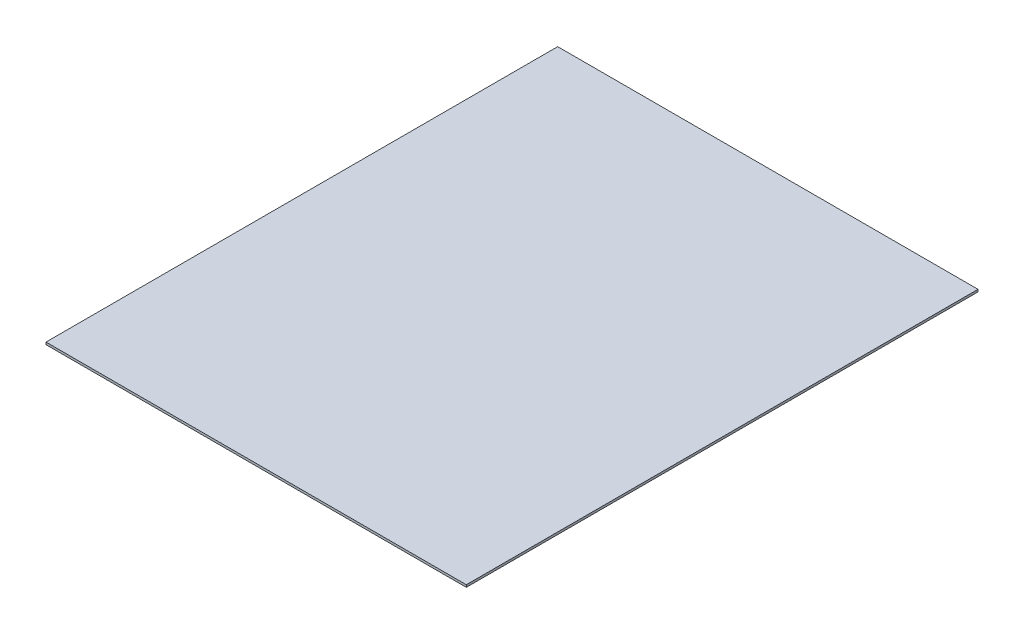
SolidWorks part; units mm, degrees
material "6061-T6 (SS)"
ref_plane "Front Plane" through (0, 0, 0) normal (0, 0, 1) x (1, 0, 0)
ref_plane "Top Plane" through (0, 0, 0) normal (0, 1, 0) x (1, 0, 0)
ref_plane "Right Plane" through (0, 0, 0) normal (1, 0, 0) x (0, 0, -1)
ref_plane "Plane1" through (0, -25.4, 330.2) normal (0, 1, 0) x (1, 0, 0)
sketch "Sketch1" plane through (0, -25.4, 330.2) normal (0, 1, 0) x (1, 0, 0)
  line L1 (292.1, 685.8) -> (-292.1, 685.8)
  line L2 (292.1, 685.8) -> (292.1, -25.4)
  line L3 (292.1, -25.4) -> (-292.1, -25.4)
  line L4 (-292.1, 685.8) -> (-292.1, -25.4)
  line L5 (292.1, 685.8) -> (-292.1, -25.4) construction
  line L6 (292.1, -25.4) -> (-292.1, 685.8) construction
  point P0 (0, 330.2)
extrude "Boss-Extrude1" add sketch "Sketch1" against normal blind 3.175
